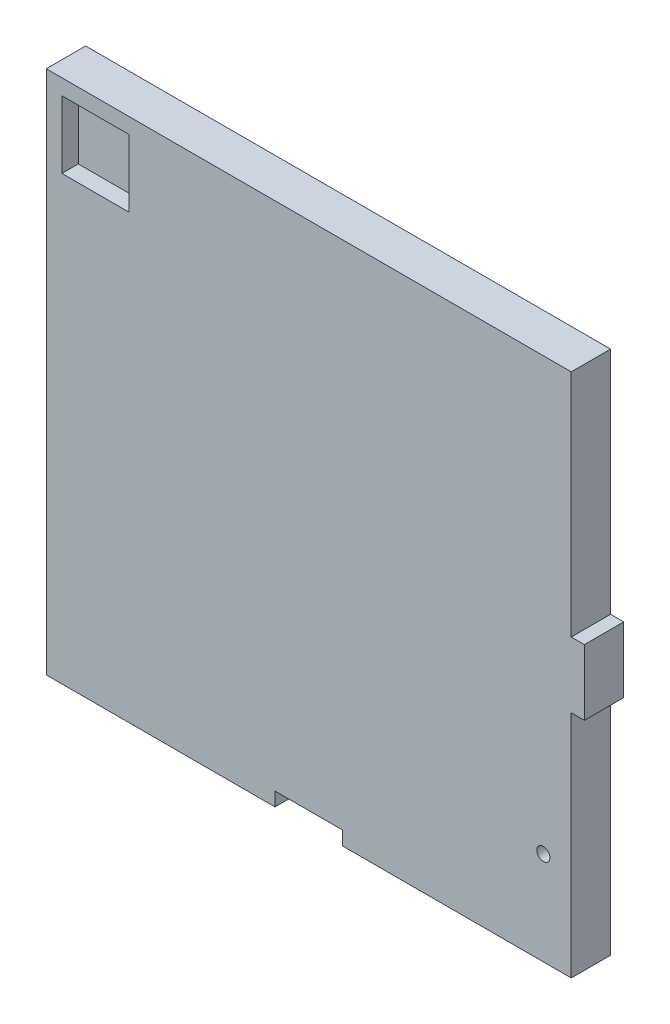
SolidWorks part; units mm, degrees
ref_plane "Front Plane" through (0, 0, 0) normal (0, 0, 1) x (1, 0, 0)
ref_plane "Top Plane" through (0, 0, 0) normal (0, 1, 0) x (1, 0, 0)
ref_plane "Right Plane" through (0, 0, 0) normal (1, 0, 0) x (0, 0, -1)
sketch "Sketch1" plane through (0, 0, 0) normal (0, 0, 1) x (1, 0, 0)
  line L0 (0, 0) -> (69.7, 0)
  line L1 (69.7, 0) -> (69.7, 4.2)
  line L2 (69.7, 4.2) -> (90.3, 4.2)
  line L3 (90.3, 4.2) -> (90.3, 0)
  line L4 (90.3, 0) -> (160, 0)
  line L5 (160, 0) -> (160, 70)
  line L6 (160, 70) -> (164, 70)
  line L7 (164, 70) -> (164, 90)
  line L8 (164, 90) -> (160, 90)
  line L9 (160, 90) -> (160, 160)
  line L10 (160, 160) -> (90, 160)
  line L11 (0, 90.3) -> (0, 69.7)
  line L12 (70, 160) -> (90, 160)
  line L14 (70, 160) -> (0, 160)
  line L15 (0, 160) -> (0, 90.3)
  line L19 (0, 69.7) -> (0, 0)
  circle A0 centre (151.5, 28.5) radius 2
  dimension "D1" = 4
extrude "Boss-Extrude1" add sketch "Sketch1" along normal blind 12
sketch "Sketch2" plane through (0, 0, 12) normal (0, 0, 1) x (1, 0, 0)
  line L0 (4.75, 134.75) -> (25.25, 134.75)
  line L1 (25.25, 134.75) -> (25.25, 155.25)
  line L2 (25.25, 155.25) -> (4.75, 155.25)
  line L3 (4.75, 155.25) -> (4.75, 134.75)
extrude "Cut-Extrude1" cut sketch "Sketch2" against normal blind 5
sketch "Sketch4" plane through (0, 0, 0) normal (0, 0, -1) x (-1, 0, 0)
  circle A0 centre (-151.5, 28.5) radius 3.45
  dimension "D1" = 6.9
extrude "Cut-Extrude2" cut sketch "Sketch4" against normal blind 8
